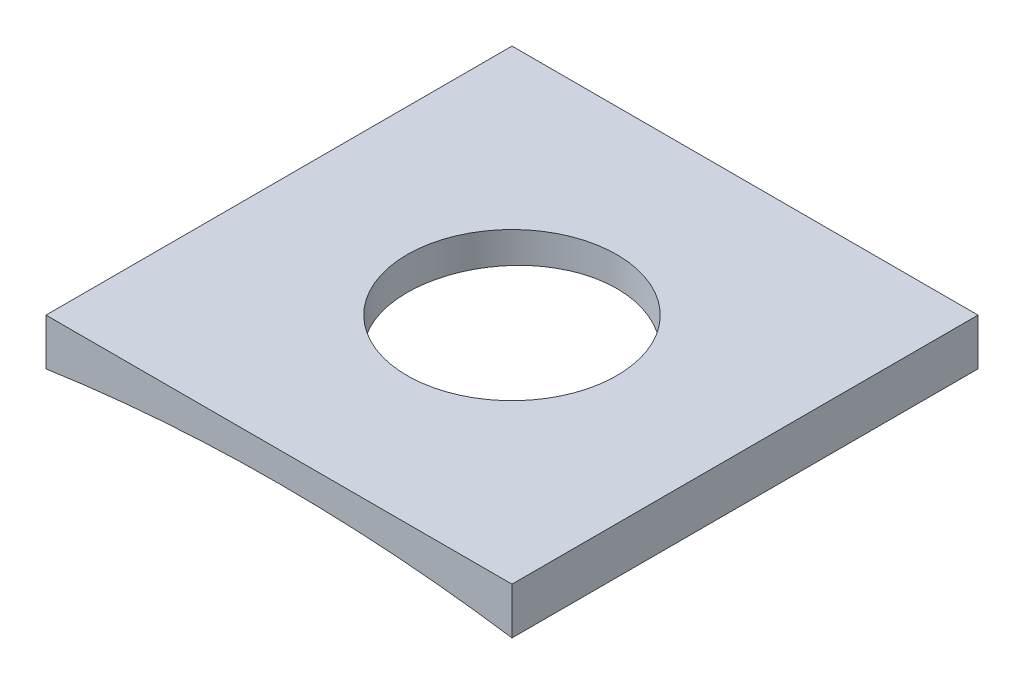
SolidWorks part; units mm, degrees
ref_plane "Front Plane" through (0, 0, 0) normal (0, 0, 1) x (1, 0, 0)
ref_plane "Top Plane" through (0, 0, 0) normal (0, 1, 0) x (1, 0, 0)
ref_plane "Right Plane" through (0, 0, 0) normal (1, 0, 0) x (0, 0, -1)
sketch "Sketch1" plane through (0, 0, 0) normal (0, 0, 1) x (1, 0, 0)
  line L0 (-5, 0) -> (5, 0)
  line L1 (-5, 0) -> (-5, -1)
  line L2 (5, 0) -> (5, -1)
  arc A0 (-5, -1) -> (5, -1) centre (0, -34.7314) cw
  point P2 (0, 0)
  point P7 (11.3159, -3.7814)
  point P8 (5, -7.7355)
  point P9 (5, -2.2113)
  dimension "D1" = 34.1
  dimension "D2" = 10
  dimension "D3" = 1
extrude "Boss-Extrude1" add sketch "Sketch1" along normal mid plane 10
sketch "Sketch2" plane through (0, 0, 0) normal (0, 1, 0) x (1, 0, 0)
  circle A0 centre (0, 0) radius 2.25
  dimension "D1" = 4.5
extrude "Cut-Extrude1" cut sketch "Sketch2" against normal through all
